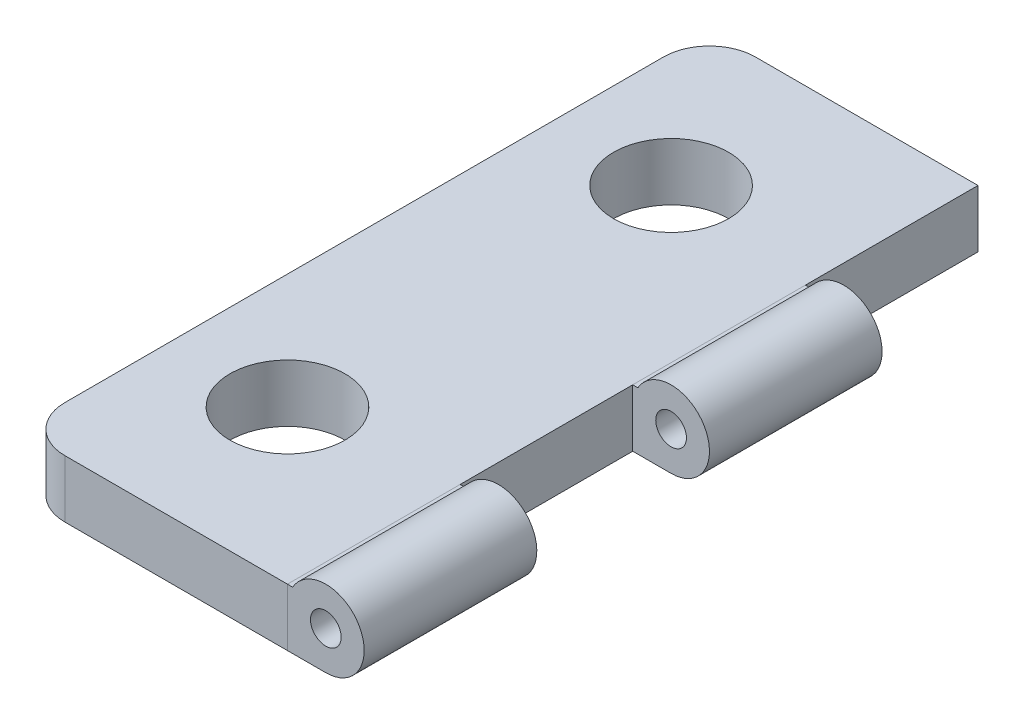
SolidWorks part; units mm, degrees
material "Простая углеродистая сталь"
ref_plane "Спереди" through (0, 0, 0) normal (0, 0, 1) x (1, 0, 0)
ref_plane "Сверху" through (0, 0, 0) normal (0, 1, 0) x (1, 0, 0)
ref_plane "Справа" through (0, 0, 0) normal (1, 0, 0) x (0, 0, -1)
sketch "Эскиз1" plane through (0, 0, 0) normal (0, 1, 0) x (1, 0, 0)
  line L0 (0, 1.2) -> (0, 16.8)
  line L1 (1.2, 18) -> (7, 18)
  line L2 (7, 18) -> (7, 13.5)
  line L3 (7, 13.5) -> (9, 13.5)
  line L4 (9, 13.5) -> (9, 9)
  line L5 (9, 9) -> (7, 9)
  line L6 (7, 9) -> (7, 4.5)
  line L7 (7, 4.5) -> (9, 4.5)
  line L8 (9, 4.5) -> (9, 0)
  line L9 (9, 0) -> (1.2, 0)
  line L10 (7, 18) -> (7, 0)
  arc A0 (1.2, 0) -> (0, 1.2) centre (1.2, 1.2) cw
  arc A1 (1.2, 18) -> (0, 16.8) centre (1.2, 16.8) ccw
  circle A2 centre (3, 14) radius 1.5
  circle A3 centre (3, 4) radius 1.5
  point P13 (0, 0)
  dimension "D2" = 4
  dimension "D3" = 4
  dimension "D5" = 3
  dimension "D9" = 3
  dimension "D10" = 3
  dimension "D12" = 1.2
  dimension "D4" = 3
  dimension "D6" = 2
  dimension "D7" = 7
  dimension "D8" = 9
  dimension "D11" = 4.5
extrude "Бобышка-Вытянуть1" add sketch "Эскиз1" along normal blind 1.5 contours L1 A1 L0 A0 L9 L10 L6 L2 A3 A2
sketch "Sketch2" plane through (0, 0, 0) normal (0, 0, 1) x (1, 0, 0)
  line L0 (8, 1) -> (7, 1) construction
  line L2 (7, 0) -> (8, 0) construction
  line L3 (8, 0) -> (8, 1) construction
  line L4 (7, 1.5) -> (7, 0) construction
  line L5 (7, 1) -> (7, 0)
  line L6 (7, 0) -> (8, 0)
  line L7 (7, 1.5) -> (7.134, 1.5)
  circle A0 centre (8, 1) radius 1
  circle A1 centre (8, 1) radius 0.4
  line M5 (7, 0) -> (7, 1.5)
  dimension "D1" = 2
  dimension "D4" = 0.8
  dimension "D2" = 1
  dimension "D3" = 1
extrude "Boss-Extrude3" add sketch "Sketch2" against normal blind 18 separate body contours A0 | A0 L7 M5 | A0 L6 M5
sketch "Sketch3" plane through (0, 0, 0) normal (0, -1, 0) x (1, 0, 0)
  line L0 (8, 0) -> (8, -18) construction
  line L1 (7.6, -18) -> (8.4, -18) construction
  line L2 (9, -4.5) -> (7, -4.5)
  line L3 (9, -4.5) -> (9, -9)
  line L4 (9, -9) -> (7, -9)
  line L5 (7, -4.5) -> (7, -9)
  line L6 (7, -13.5) -> (9, -13.5)
  line L7 (7, -13.5) -> (7, -18)
  line L8 (7, -18) -> (9, -18)
  line L9 (9, -13.5) -> (9, -18)
  point P3 (8, -4.5)
  point P4 (8, -9)
  point P5 (8, -13.5)
  point P10 (8, -4.5)
  point P11 (8, -9)
  point P16 (8, -18)
  point P17 (8, -13.5)
  point P18 (0, 0)
  dimension "D1" = 4.5
  dimension "D2" = 4.5
  dimension "D3" = 2
  dimension "D4" = 2
extrude "Cut-Extrude2" cut sketch "Sketch3" against normal blind 20
